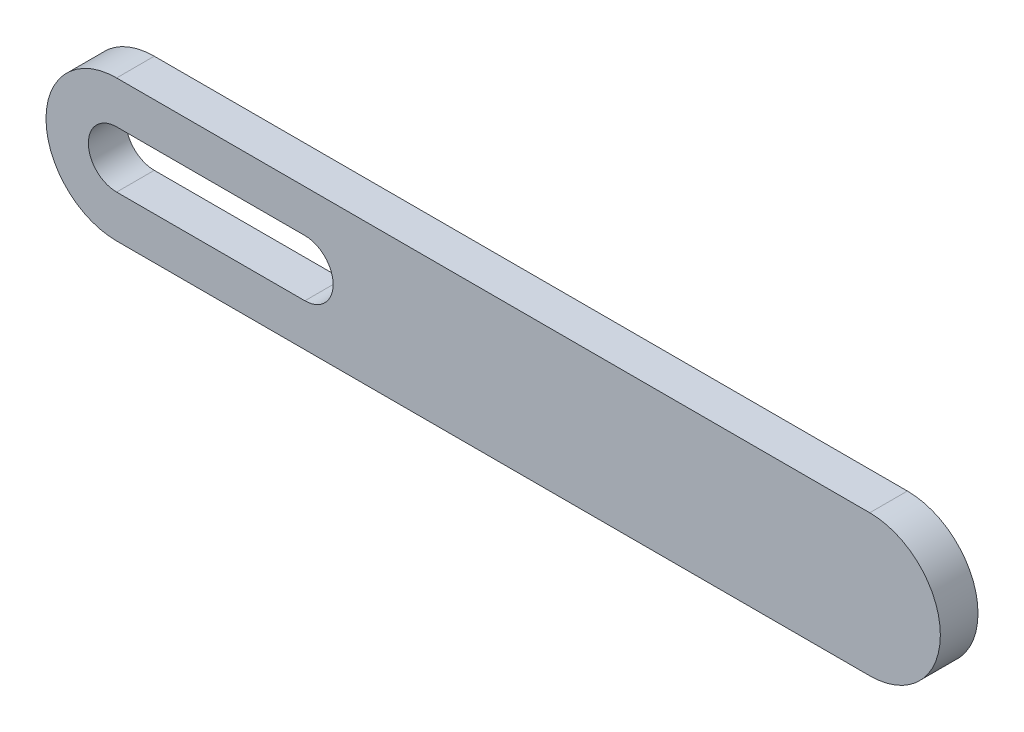
SolidWorks part; units mm, degrees
ref_plane "Front Plane" through (0, 0, 0) normal (0, 0, 1) x (1, 0, 0)
ref_plane "Top Plane" through (0, 0, 0) normal (0, 1, 0) x (1, 0, 0)
ref_plane "Right Plane" through (0, 0, 0) normal (1, 0, 0) x (0, 0, -1)
sketch "Sketch1" plane through (0, 0, 0) normal (0, 0, 1) x (1, 0, 0)
  line L0 (-376.6667, 0) -> (328.3333, 0) construction
  line L1 (0, 270) -> (0, -298.3333) construction
  line L2 (-200, 0) -> (200, 0) construction
  line L3 (-200, 37.5) -> (200, 37.5)
  line L4 (-200, -37.5) -> (200, -37.5)
  line L5 (-200, 0) -> (-100, 0) construction
  line L8 (-200, 15) -> (-100, 15)
  line L9 (-200, -15) -> (-100, -15)
  arc A0 (-200, 37.5) -> (-200, -37.5) centre (-200, 0) ccw
  arc A1 (200, -37.5) -> (200, 37.5) centre (200, 0) ccw
  arc A4 (-200, 15) -> (-200, -15) centre (-200, 0) ccw
  arc A5 (-100, -15) -> (-100, 15) centre (-100, 0) ccw
  point P7 (0, 0)
  point P14 (-150, 0)
  dimension "D5" = 15
  dimension "D1" = 200
  dimension "D2" = 200
  dimension "D3" = 400
  dimension "D4" = 100
  dimension "D6" = 75
extrude "Boss-Extrude1" add sketch "Sketch1" along normal blind 20
